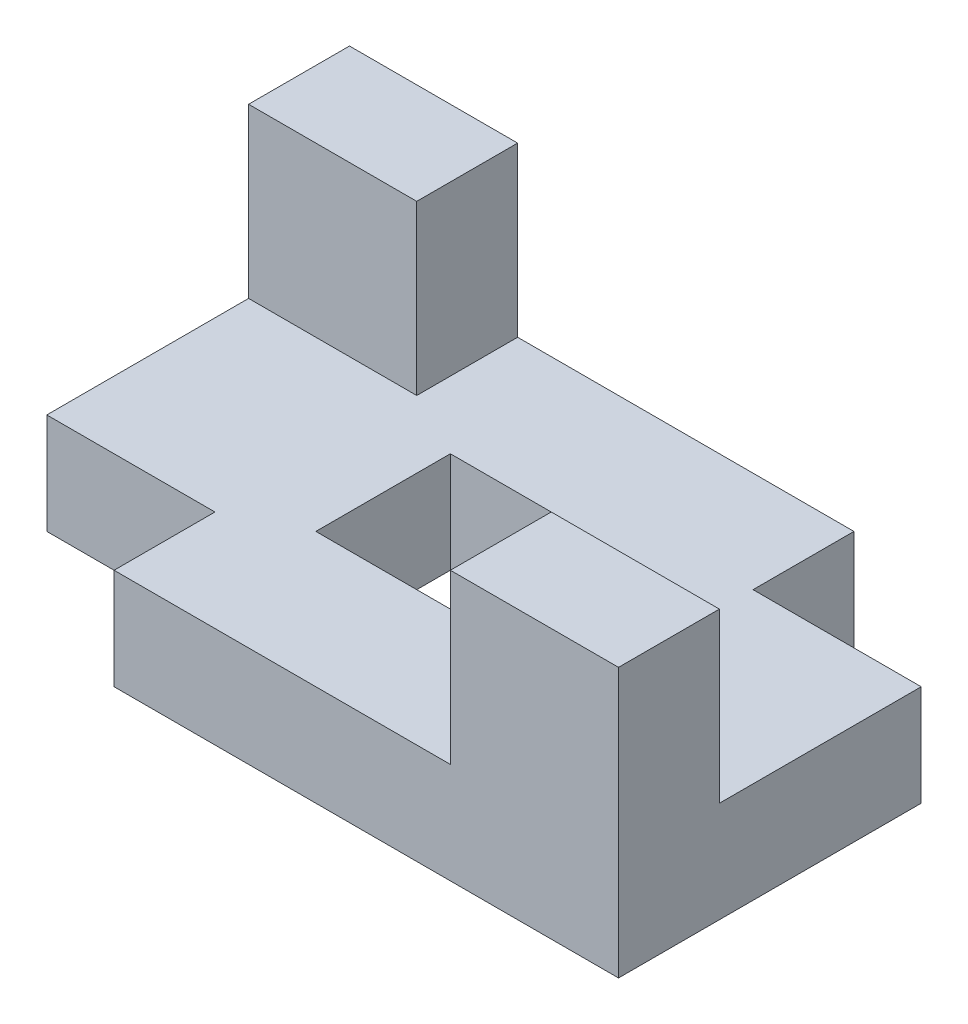
SolidWorks part; units mm, degrees
ref_plane "Front Plane" through (0, 0, 0) normal (0, 0, 1) x (1, 0, 0)
ref_plane "Top Plane" through (0, 0, 0) normal (0, 1, 0) x (1, 0, 0)
ref_plane "Right Plane" through (0, 0, 0) normal (1, 0, 0) x (0, 0, -1)
sketch "Sketch1" plane through (0, 0, 0) normal (0, 1, 0) x (1, 0, 0)
  line L1 (-50, 30) -> (50, 30)
  line L2 (-50, 30) -> (-50, -30)
  line L3 (-50, -30) -> (50, -30)
  line L4 (50, 30) -> (50, -30)
  dimension "D1" = 100
  dimension "D2" = 60
  dimension "D3" = 50
  dimension "D4" = 30
extrude "Boss-Extrude1" add sketch "Sketch1" along normal blind 15 contours L3 L4 L1 L2
sketch "Sketch2" plane through (0, 15, 0) normal (0, 1, 0) x (1, 0, 0)
  line L1 (-50, 30) -> (-25, 30)
  line L2 (-50, 30) -> (-50, 15)
  line L3 (-50, 15) -> (-25, 15)
  line L4 (-25, 30) -> (-25, 15)
  line L5 (50, -30) -> (25, -30)
  line L6 (50, -30) -> (50, -15)
  line L7 (50, -15) -> (25, -15)
  line L8 (25, -30) -> (25, -15)
  point P10 (0, 0)
  dimension "D1" = 15
  dimension "D2" = 25
extrude "Boss-Extrude2" add sketch "Sketch2" along normal blind 25
sketch "Sketch4" plane through (0, 15, 0) normal (0, 1, 0) x (1, 0, 0)
  line L1 (-50, -30) -> (-25, -30)
  line L2 (-50, -30) -> (-50, -15)
  line L3 (-50, -15) -> (-25, -15)
  line L4 (-25, -30) -> (-25, -15)
  line L5 (50, 30) -> (25, 30)
  line L6 (50, 30) -> (50, 15)
  line L7 (50, 15) -> (25, 15)
  line L8 (25, 30) -> (25, 15)
  dimension "D1" = 15
  dimension "D2" = 25
extrude "Cut-Extrude1" cut sketch "Sketch4" against normal blind 23
sketch "Sketch5" plane through (0, 15, 0) normal (0, 1, 0) x (1, 0, 0)
  line L0 (-50, 15) -> (-50, -15) construction
  line L1 (-15, 10) -> (15, 10)
  line L2 (-15, 10) -> (-15, -10)
  line L3 (-15, -10) -> (15, -10)
  line L4 (15, 10) -> (15, -10)
  line L5 (-25, -30) -> (25, -30) construction
  point P6 (-50, 0)
  point P9 (0, -30)
  dimension "D1" = 35
  dimension "D2" = 20
  dimension "D3" = 20
  dimension "D4" = 30
extrude "Cut-Extrude3" cut sketch "Sketch5" against normal blind 45 contours L3 L4 L1 L2
